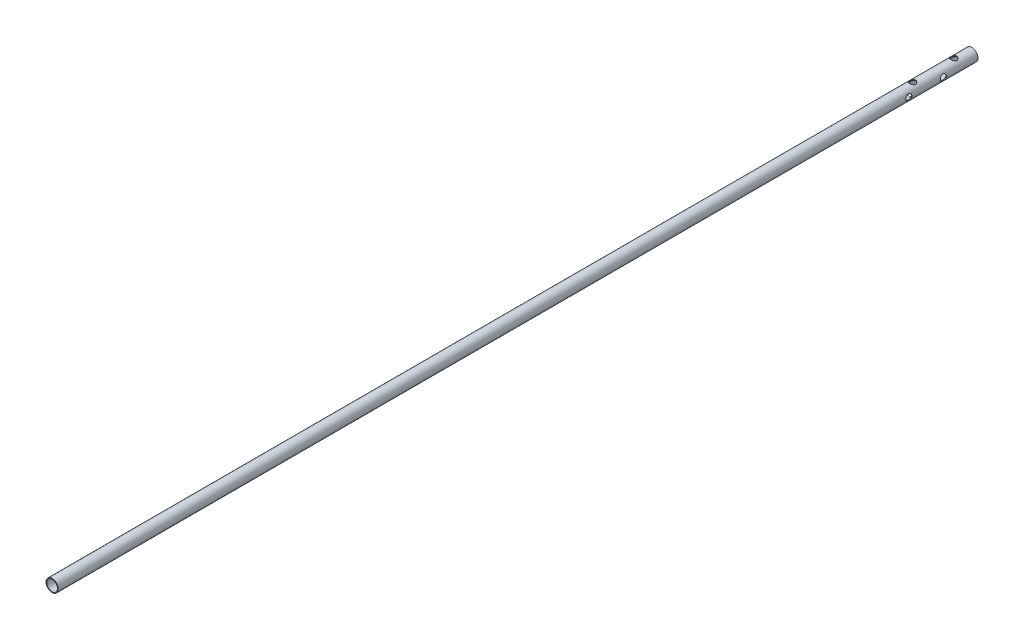
SolidWorks part; units mm, degrees
material "carbon fiber"
ref_plane "Front Plane" through (0, 0, 0) normal (0, 0, 1) x (1, 0, 0)
ref_plane "Top Plane" through (0, 0, 0) normal (0, 1, 0) x (1, 0, 0)
ref_plane "Right Plane" through (0, 0, 0) normal (1, 0, 0) x (0, 0, -1)
sketch "Эскиз1" plane through (0, 0, 0) normal (0, 0, 1) x (1, 0, 0)
  circle A0 centre (0, 0) radius 8
  circle A1 centre (0, 0) radius 7
  dimension "D1" = 16
  dimension "D2" = 1
extrude "Бобышка-Вытянуть1" add sketch "Эскиз1" along normal mid plane 1200
sketch "Эскиз2" plane through (0, 0, 0) normal (1, 0, 0) x (0, 0, -1)
  line L0 (620.3264, 0) -> (366.7106, 0) construction
  line L1 (600, -8) -> (600, 8) construction
  circle A0 centre (510, 0) radius 4
  circle A1 centre (555, 0) radius 4
  dimension "D1" = 8
  dimension "D2" = 8
  dimension "D3" = 45
  dimension "D4" = 90
  dimension "D5" = 45
extrude "Вырез-Вытянуть1" cut sketch "Эскиз2" against normal through all both and the other way through all
sketch "Эскиз3" plane through (0, 0, 0) normal (0, 1, 0) x (1, 0, 0)
  line L0 (0, 600) -> (0, 479.9801) construction
  line L1 (7, 600) -> (-7, 600) construction
  circle A0 centre (0, 555) radius 3.2304 construction
  circle A1 centre (0, 576.5) radius 4
  circle A2 centre (0, 522.5) radius 4
  dimension "D1" = 45
  dimension "D2" = 21.5
  dimension "D3" = 8
  dimension "D4" = 54
extrude "Вырез-Вытянуть2" cut sketch "Эскиз3" against normal through all both and the other way through all
